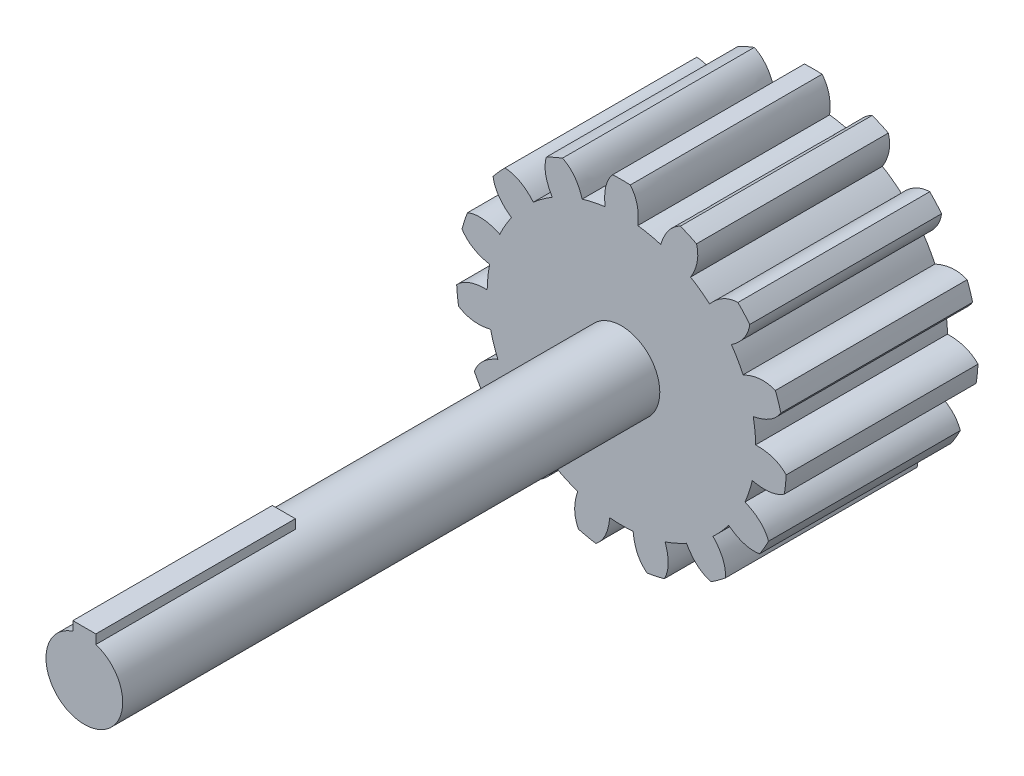
SolidWorks part; units mm, degrees
ref_plane "前视基准面" through (0, 0, 0) normal (0, 0, 1) x (1, 0, 0)
ref_plane "上视基准面" through (0, 0, 0) normal (0, 1, 0) x (1, 0, 0)
ref_plane "右视基准面" through (0, 0, 0) normal (1, 0, 0) x (0, 0, -1)
sketch "草图2" plane through (0, 0, 0) normal (0, 0, 1) x (1, 0, 0)
  circle A0 centre (0, 0) radius 17.5
  dimension "D1" = 35
extrude "凸台-拉伸2" add sketch "草图2" along normal blind 25
sketch "草图3" plane through (0, 0, 25) normal (0, 0, 1) x (1, 0, 0)
  circle A0 centre (0, 0) radius 5
  dimension "D1" = 10
sketch "草图4" plane through (0, 0, 0) normal (0, 0, -1) x (-1, 0, 0)
  arc A4 (1.1527, 21.4691) -> (-1.1527, 21.4691) centre (0, 0) ccw
  circle A5 centre (0, 0) radius 17.5 construction
  arc A6 (2.1327, 17.3696) -> (-2.1327, 17.3696) centre (0, 0) ccw
  spline S0 degree 2 poles (-2.1327, 17.3696) (-2.448, 19.9375) (-1.1527, 21.4691) knots 0 0 0 0.686912 0.686912 0.686912
  spline S1 degree 2 poles (2.1327, 17.3696) (2.448, 19.9375) (1.1527, 21.4691) knots 0 0 0 0.686912 0.686912 0.686912
  dimension "D4" = 43
extrude "凸台-拉伸3" add sketch "草图4" against normal blind 25
pattern_circular "阵列(圆周)1" count 15 over 360 about axis through (0, 0, 0) along (0, 0, 1) of "凸台-拉伸3"
extrude "凸台-拉伸4" add sketch "草图3" along normal blind 70
sketch "草图7" plane through (0, 0, 95) normal (0, 0, 1) x (1, 0, 0)
  line L3 (1.5, 4.7697) -> (1.5, 5.9697)
  line L4 (-1.5, 4.7697) -> (-1.5, 5.9697)
  line L5 (-1.5, 5.9697) -> (1.5, 5.9697)
  circle A0 centre (0, 0) radius 5 construction
  arc A1 (1.5, 4.7697) -> (-1.5, 4.7697) centre (0, 0) ccw
  dimension "D3" = 1.2
extrude "凸台-拉伸5" add sketch "草图7" against normal blind 26
